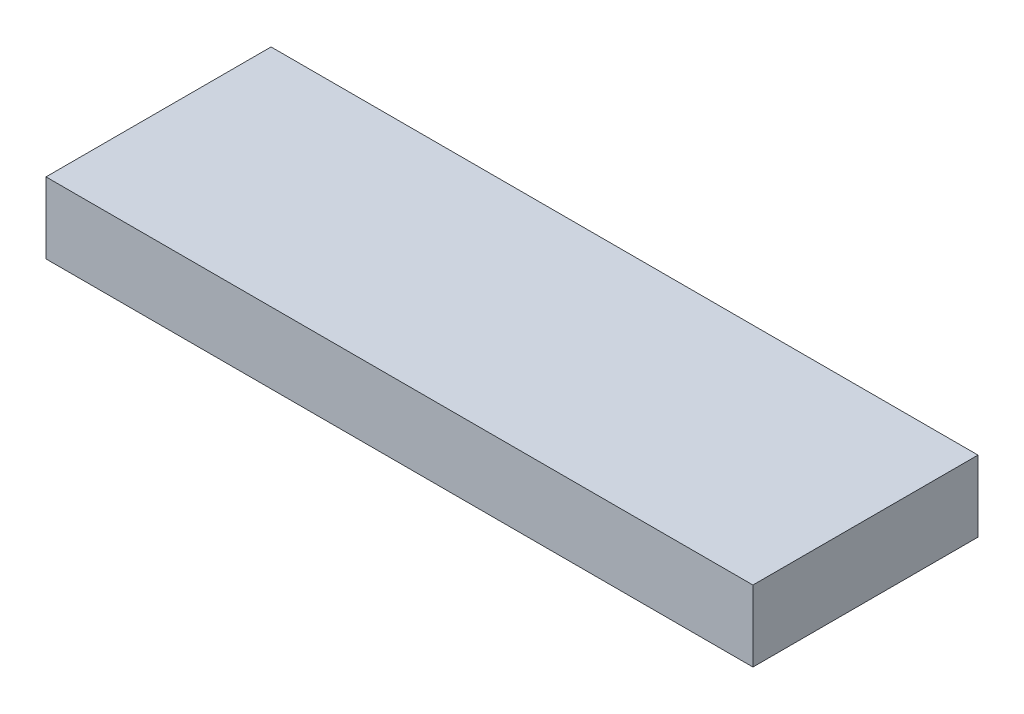
SolidWorks part; units mm, degrees
material "MDF"
ref_plane "Front Plane" through (0, 0, 0) normal (0, 0, 1) x (1, 0, 0)
ref_plane "Top Plane" through (0, 0, 0) normal (0, 1, 0) x (1, 0, 0)
ref_plane "Right Plane" through (0, 0, 0) normal (1, 0, 0) x (0, 0, -1)
sketch "Sketch1" plane through (0, 0, 0) normal (0, 0, 1) x (1, 0, 0)
  line L1 (133.8612, 0) -> (323.3388, 0)
  line L2 (133.8612, 0) -> (133.8612, -19.05)
  line L3 (133.8612, -19.05) -> (323.3388, -19.05)
  line L4 (323.3388, 0) -> (323.3388, -19.05)
  line L5 (323.3388, -298.45) -> (323.3388, 20.8246) construction
  line L6 (133.8612, -298.45) -> (133.8612, 20.8246) construction
  line L8 (456.6888, 0) -> (0.5112, 0) construction
  point P5 (0, 0)
  point P6 (0, 0)
  point P7 (0, 0)
  point P8 (0, 0)
  dimension "D1" = 19.05
extrude "Boss-Extrude1" add sketch "Sketch1" along normal up to surface (60.325 mm away)
